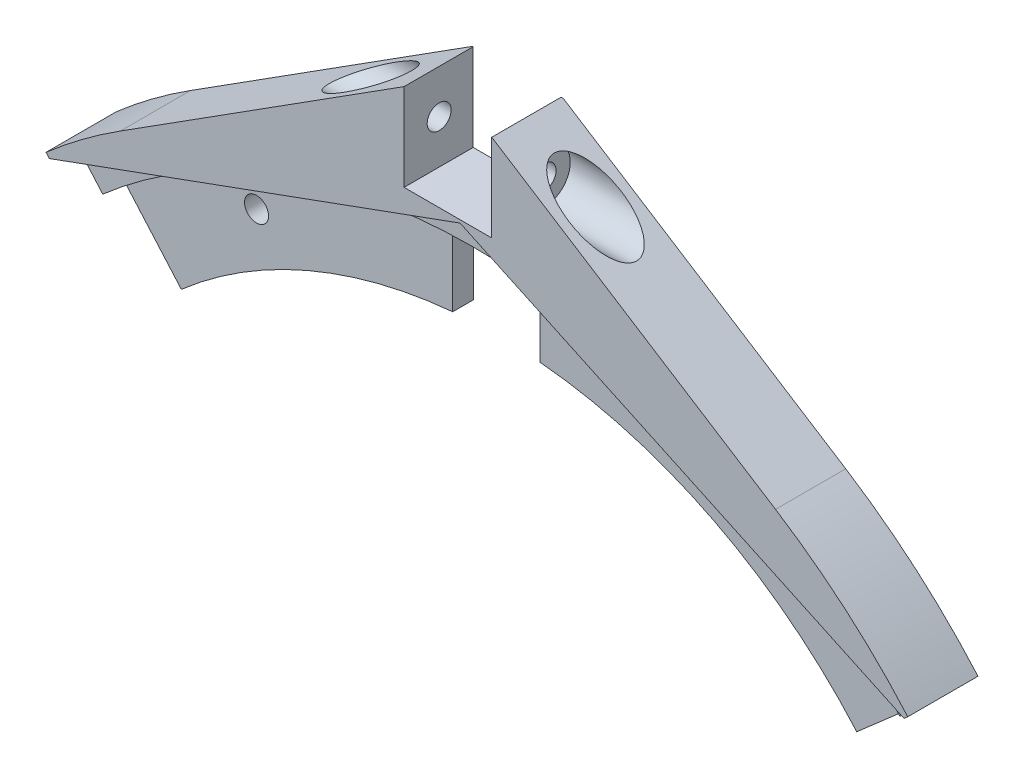
SolidWorks part; units mm, degrees
ref_plane "Front Plane" through (0, 0, 0) normal (0, 0, 1) x (1, 0, 0)
ref_plane "Top Plane" through (0, 0, 0) normal (0, 1, 0) x (1, 0, 0)
ref_plane "Right Plane" through (0, 0, 0) normal (1, 0, 0) x (0, 0, -1)
sketch "Sketch1" plane through (0, 0, 0) normal (0, 0, 1) x (1, 0, 0)
  line L0 (0, 284.5128) -> (0, -315.9314) construction
  line L1 (-464.297, 0) -> (544.589, 0) construction
  line L2 (2.7918, 138.8272) -> (104.5532, 91.375)
  line L9 (2.7918, 138.8272) -> (-91.375, 104.5532)
  line L11 (-138.8272, 2.7918) -> (-104.5532, -91.375)
  line L13 (-2.7918, -138.8272) -> (91.375, -104.5532)
  line L15 (138.8272, -2.7918) -> (104.5532, 91.375)
  line L17 (138.8272, -2.7918) -> (91.375, -104.5532)
  line L18 (-2.7918, -138.8272) -> (-104.5532, -91.375)
  line L19 (-138.8272, 2.7918) -> (-91.375, 104.5532)
  line L20 (103.344, 94.6973) -> (54.7291, 117.3669)
  line L21 (-117.3669, 54.7291) -> (-140.0364, 6.1141)
  line L22 (-103.344, -94.6973) -> (-54.7291, -117.3669)
  line L23 (94.6973, -103.344) -> (117.3669, -54.7291)
  circle A0 centre (0, 0) radius 129.5 construction
  circle A2 centre (0, 0) radius 129.5
  circle A3 centre (0, 0) radius 109.75
  dimension "D2" = 259
  dimension "D3" = 219.5
  dimension "D1" = 70
  dimension "D4" = 259
  dimension "D5" = 254
  dimension "D6" = 4
sketch "Sketch2" plane through (0, 0, 0) normal (0, 0, 1) x (1, 0, 0)
  circle A2 centre (0, 0) radius 109.75
  circle A3 centre (0, 0) radius 129.5
  point P1 (114.75, 0)
  point P3 (0, 0)
  point P9 (104.9544, 32.0878)
  dimension "D1" = 219.5
  dimension "D2" = 259
sketch "Sketch3" plane through (0, 0, 0) normal (0, 0, 1) x (1, 0, 0)
  line L0 (0, 216.6703) -> (0, -179.3029) construction
  line L1 (2.7918, 138.8272) -> (124.3623, 138.8272) construction
  line L2 (0, 284.5128) -> (0, -315.9314) construction
  line L4 (-261.0178, 0) -> (186.7113, 0) construction
  line L5 (-464.297, 0) -> (544.589, 0) construction
  line L22 (-157.8941, 129.5) -> (159.8749, 129.5) construction
  line L23 (0, 0) -> (-64.3319, 176.7503) construction
  line L40 (-132.8743, 89.4487) -> (56.0531, 158.2127) construction
  line L41 (129.5, -10) -> (109.5, -10)
  line L42 (10, 129.5) -> (-10, 129.5)
  line L43 (10, 129.5) -> (10, 109.5)
  line L44 (10, 109.5) -> (-10, 109.5)
  line L45 (-10, 129.5) -> (-10, 109.5)
  line L46 (129.5, -10) -> (129.5, 10)
  line L47 (129.5, 10) -> (109.5, 10)
  line L48 (109.5, -10) -> (109.5, 10)
  line L49 (-10, -129.5) -> (-10, -109.5)
  line L50 (-10, -129.5) -> (10, -129.5)
  line L51 (10, -129.5) -> (10, -109.5)
  line L52 (-10, -109.5) -> (10, -109.5)
  line L53 (-129.5, 10) -> (-109.5, 10)
  line L54 (-129.5, 10) -> (-129.5, -10)
  line L55 (-129.5, -10) -> (-109.5, -10)
  line L56 (-109.5, 10) -> (-109.5, -10)
  line L57 (-62.4545, 104.4377) -> (46.2898, 144.0174) construction
  line L62 (-10, 139.5) -> (10, 139.5)
  line L63 (-10, 139.5) -> (-10, 159.5)
  line L64 (-10, 159.5) -> (10, 159.5)
  line L65 (10, 139.5) -> (10, 159.5)
  circle A8 centre (-54.9668, 107.163) radius 2.75
  circle A9 centre (-26.776, 117.4236) radius 2.75
  circle A10 centre (107.163, 54.9668) radius 2.75
  circle A11 centre (117.4236, 26.776) radius 2.75
  circle A12 centre (54.9668, -107.163) radius 2.75
  circle A13 centre (26.776, -117.4236) radius 2.75
  circle A14 centre (-107.163, -54.9668) radius 2.75
  circle A15 centre (-117.4236, -26.776) radius 2.75
  dimension "D8" = 5.5
  dimension "D9" = 15
  dimension "D1" = 129.5
  dimension "D2" = 20
  dimension "D3" = 70
  dimension "D4" = 129.5
  dimension "D5" = 20
  dimension "D7" = 10
  dimension "D6" = 20
  dimension "D10" = 10
  dimension "D13" = 20
  dimension "D14" = 20
  dimension "D15" = 10
  dimension "D16" = 10
  dimension "D12" = 4
  dimension "D11" = 4
sketch "Sketch4" plane through (0, 0, 0) normal (0, 0, 1) x (1, 0, 0)
  line L0 (0, 247.7886) -> (0, -153.99) construction
  line L1 (0, 284.5128) -> (0, -315.9314) construction
  line L2 (-190.7853, 0) -> (227.3701, 0) construction
  line L3 (-464.297, 0) -> (544.589, 0) construction
  line L4 (2.7918, 138.8272) -> (104.5532, 91.375) construction
  line L5 (2.7918, 138.8272) -> (-91.375, 104.5532) construction
  line L6 (2.7918, 138.8272) -> (104.5532, 91.375)
  line L7 (2.7918, 138.8272) -> (-91.375, 104.5532)
  line L8 (0, 0) -> (-91.375, 104.5532) construction
  line L9 (0, 0) -> (104.5532, 91.375) construction
  line L10 (104.5532, 91.375) -> (105.4152, 92.1284)
  line L11 (-91.375, 104.5532) -> (-92.1284, 105.4152)
  arc A1 (105.4152, 92.1284) -> (-92.1284, 105.4152) centre (0, 0) ccw
  dimension "D1" = 280
extrude "Boss-Extrude1" add sketch "Sketch4" along normal blind 6.1
sketch "Sketch5" plane through (0, 0, 0) normal (0, 0, 1) x (1, 0, 0)
  line L0 (0, 161.9102) -> (0, -158.9824) construction
  line L1 (0, 284.5128) -> (0, -315.9314) construction
  line L6 (2.7918, 138.8272) -> (104.5532, 91.375) construction
  line L7 (30.7222, 125.803) -> (76.6229, 104.3992)
  line L9 (105.4152, 92.1284) -> (97.5091, 85.2187)
  line L10 (-85.2187, 97.5091) -> (-92.1284, 105.4152)
  arc A3 (105.4152, 92.1284) -> (-92.1284, 105.4152) centre (0, 0) ccw construction
  arc A4 (105.4152, 92.1284) -> (-92.1284, 105.4152) centre (0, 0) ccw
  arc A6 (30.7222, 125.803) -> (-85.2187, 97.5091) centre (0, 0) ccw
  arc A7 (97.5091, 85.2187) -> (76.6229, 104.3992) centre (0, 0) ccw
extrude "Boss-Extrude4" add sketch "Sketch5" against normal blind 5
sketch "Sketch6" plane through (0, 0, -5) normal (0, 0, -1) x (-1, 0, 0)
  line L2 (0, 169.5523) -> (0, -199.0298) construction
  line L3 (0, 284.5128) -> (0, -315.9314) construction
  line L4 (-232.6153, 0) -> (198.4747, 0) construction
  line L5 (464.297, 0) -> (-544.589, 0) construction
  line L6 (-10, 129.5) -> (10, 129.5) construction
  line L7 (-10, 129.5) -> (10, 129.5)
  line L8 (-10, 129.5) -> (-10, 109.2684)
  line L9 (10, 129.5) -> (10, 109.2684)
  line L11 (-105.4152, 92.1284) -> (-82.6192, 72.2056)
  line L12 (92.1284, 105.4152) -> (72.2056, 82.6192)
  arc A0 (92.1284, 105.4152) -> (-105.4152, 92.1284) centre (0, 0) ccw construction
  arc A1 (92.1284, 105.4152) -> (-105.4152, 92.1284) centre (0, 0) ccw
  arc A2 (72.2056, 82.6192) -> (10, 109.2684) centre (0, 0) ccw
  circle A3 centre (54.9668, 107.163) radius 2.75 construction
  circle A4 centre (54.9668, 107.163) radius 2.75
  arc A5 (-10, 109.2684) -> (-82.6192, 72.2056) centre (0, 0) ccw
  dimension "D1" = 219.45
extrude "Boss-Extrude5" add sketch "Sketch6" along normal blind 5
sketch "Sketch7" plane through (0, 0, 0) normal (0, 0, 1) x (1, 0, 0)
  line L0 (0, 0) -> (105.9278, 126.2398) construction
  line L1 (-464.297, 0) -> (544.589, 0) construction
  circle A0 centre (76.8131, 91.5423) radius 2.75
  dimension "D2" = 5.5
  dimension "D3" = 119.5
  dimension "D1" = 50
extrude "Cut-Extrude1" cut sketch "Sketch7" against normal through all
sketch "Sketch8" plane through (0, 0, 0) normal (0, 0, 1) x (1, 0, 0)
  line L0 (-375.8886, 0) -> (366.7667, 0) construction
  line L2 (-464.297, 0) -> (544.589, 0) construction
  line L3 (0, 318.2337) -> (0, -226.325) construction
  line L4 (0, 284.5128) -> (0, -315.9314) construction
  line L5 (-10.05, 139.6388) -> (-10.05, 159.5)
  line L6 (-10.05, 159.5) -> (-75.1007, 118.152)
  line L7 (10.05, 139.6388) -> (10.05, 159.5)
  line L8 (10.05, 159.5) -> (75.1007, 118.152)
  arc A0 (105.4152, 92.1284) -> (-92.1284, 105.4152) centre (0, 0) ccw construction
  arc A1 (-10.05, 139.6388) -> (-75.1007, 118.152) centre (0, 0) ccw
  arc A2 (10.05, 139.6388) -> (75.1007, 118.152) centre (0, 0) cw
  dimension "D1" = 10.05
  dimension "D2" = 159.5
extrude "Boss-Extrude6" add sketch "Sketch8" along normal up to surface and the other way up to surface
sketch "Sketch9" plane through (0, 0, 0) normal (0, 0, 1) x (1, 0, 0)
  line L0 (0, 206.3471) -> (0, 78.478) construction
  line L1 (0, 284.5128) -> (0, -315.9314) construction
  line L2 (-464.297, 0) -> (544.589, 0) construction
  line L3 (-10.05, 139.5) -> (10.05, 139.5)
  line L4 (-10.05, 139.5) -> (-10.05, 155.557)
  line L5 (-10.05, 155.557) -> (10.05, 155.557)
  line L6 (10.05, 139.5) -> (10.05, 155.557)
  dimension "D1" = 139.5
  dimension "D2" = 20.1
  dimension "D3" = 10.05
extrude "Cut-Extrude2" cut sketch "Sketch9" against normal through all both and the other way through all
sketch "Sketch10" plane through (-10.05, 0, 0) normal (1, 0, 0) x (0, 0, -1)
  line L0 (-23.3474, 139.5) -> (34.7765, 139.5) construction
  line L1 (1.95, 166.1136) -> (1.95, 133.4254) construction
  line L2 (-6.1, 118.152) -> (-6.1, 159.5) construction
  circle A0 centre (1.95, 149.5) radius 2.75
  dimension "D3" = 5.5
  dimension "D4" = 10
  dimension "D1" = 139.5
  dimension "D2" = 8.05
extrude "Cut-Extrude3" cut sketch "Sketch10" against normal through all both and the other way through all
ref_plane "Plane1" through (14, 0, 0) normal (1, 0, 0) x (0, 0, -1)
sketch "Sketch11" plane through (14, 0, 0) normal (1, 0, 0) x (0, 0, -1)
  circle A0 centre (1.95, 149.5) radius 6
  dimension "D1" = 12
extrude "Cut-Extrude4" cut sketch "Sketch11" along normal through all
ref_plane "Plane2" through (-14, 0, 0) normal (1, 0, 0) x (0, 0, -1)
sketch "Sketch12" plane through (-14, 0, 0) normal (1, 0, 0) x (0, 0, -1)
  circle A0 centre (1.95, 149.5) radius 6
  dimension "D1" = 12
extrude "Cut-Extrude5" cut sketch "Sketch12" against normal through all
chamfer "Chamfer1" distance 0.25 angle 45 6 edges at (10, 119.3842, -10) (-10, 119.3842, -10) (0, 129.5, -10) (-10.05, 149.5, -10) (0, 139.5, -10) (10.05, 149.5, -10)
